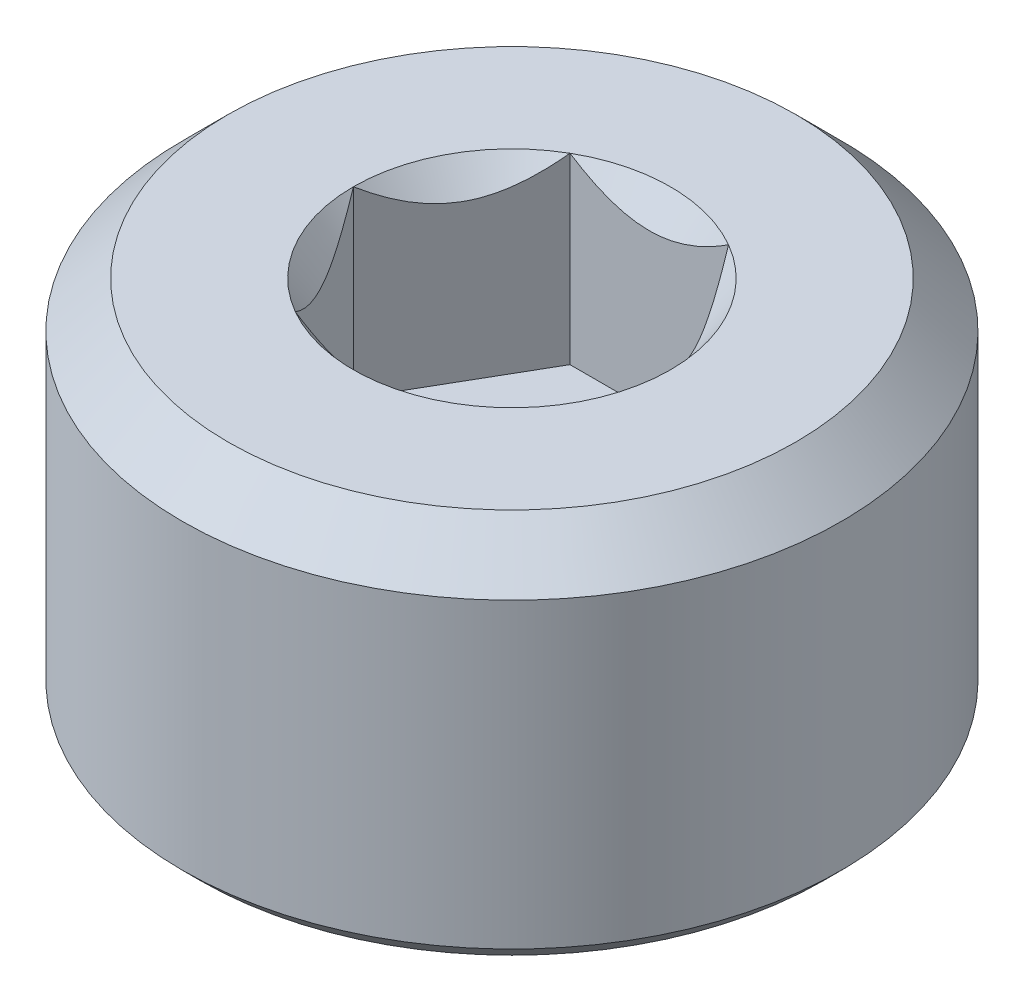
SolidWorks part; units mm, degrees
ref_plane "前视基准面" through (0, 0, 0) normal (0, 0, 1) x (1, 0, 0)
ref_plane "上视基准面" through (0, 0, 0) normal (0, 1, 0) x (1, 0, 0)
ref_plane "右视基准面" through (0, 0, 0) normal (1, 0, 0) x (0, 0, -1)
sketch "草图1" plane through (0, 0, 0) normal (0, 1, 0) x (1, 0, 0)
  circle A0 centre (0, 0) radius 3.6
  dimension "D1" = 7.2
extrude "凸台-拉伸1" add sketch "草图1" along normal blind 4
sketch "草图2" plane through (0, 4, 0) normal (0, 1, 0) x (1, 0, 0)
  line L1 (1.7321, 0) -> (0.866, 1.5)
  line L2 (0.866, 1.5) -> (-0.866, 1.5)
  line L3 (-0.866, 1.5) -> (-1.7321, 0)
  line L4 (-1.7321, 0) -> (-0.866, -1.5)
  line L5 (-0.866, -1.5) -> (0.866, -1.5)
  line L6 (0.866, -1.5) -> (1.7321, 0)
  circle A0 centre (0, 0) radius 1.5 construction
  dimension "D1" = 3
extrude "切除-拉伸1" cut sketch "草图2" against normal blind 2
sketch "草图3" plane through (0, 4, 0) normal (0, 1, 0) x (1, 0, 0)
  circle A0 centre (0, 0) radius 1.7321
ref_plane "基准面1" through (0, 3.7, 0) normal (0, 1, 0) x (1, 0, 0)
sketch "草图4" plane through (0, 3.7, 0) normal (0, 1, 0) x (1, 0, 0)
  circle A0 centre (0, 0) radius 1.5
loft "切除-放样1" cut profiles "草图3", "草图4"
chamfer "倒角1" distance 0.5 angle 45 1 edges at (0, 4, 3.6)
chamfer "倒角2" distance 0.2 angle 45 1 edges at (0, 0, 3.6)
